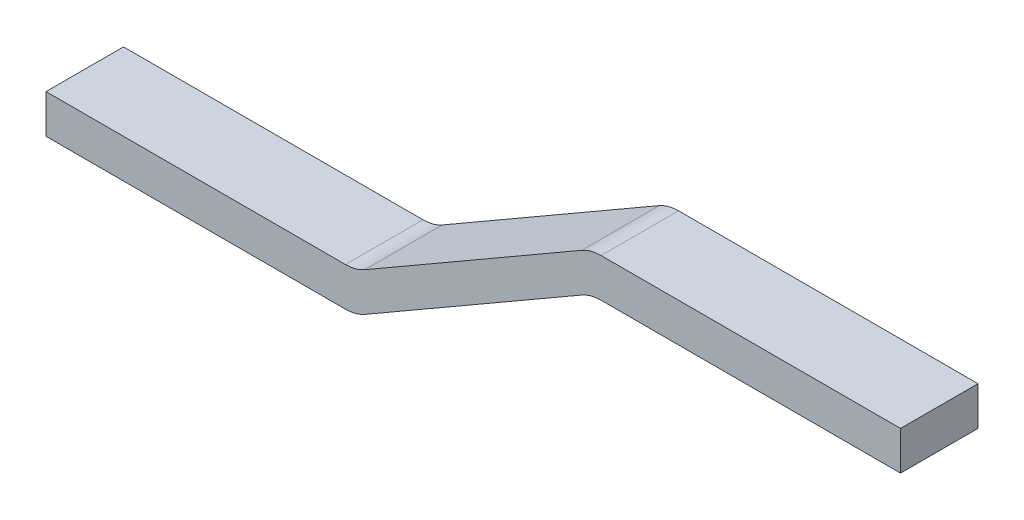
SolidWorks part; units mm, degrees
ref_plane "Plan de face" through (0, 0, 0) normal (0, 0, 1) x (1, 0, 0)
ref_plane "Plan de dessus" through (0, 0, 0) normal (0, 1, 0) x (1, 0, 0)
ref_plane "Plan de droite" through (0, 0, 0) normal (1, 0, 0) x (0, 0, -1)
sketch "Esquisse1" plane through (0, 0, 0) normal (0, 0, 1) x (1, 0, 0)
  line L0 (-20, 5) -> (20, 5)
  line L1 (20, 5) -> (50.3109, 22.5)
  line L2 (50.3109, 22.5) -> (90.3109, 22.5)
  line L3 (90.3109, 22.5) -> (90.3109, 17.5)
  line L4 (90.3109, 17.5) -> (50.3109, 17.5)
  line L5 (50.3109, 17.5) -> (20, 0)
  line L6 (20, 0) -> (-20, 0)
  line L7 (-20, 0) -> (-20, 5)
  point P10 (0, 0)
  dimension "D1" = 5
  dimension "D2" = 5
  dimension "D3" = 150
  dimension "D4" = 40
  dimension "D5" = 40
  dimension "D6" = 35
extrude "Boss.-Extru.1" add sketch "Esquisse1" along normal blind 10 contours L7 L0 L1 L2 L3 L4 L5 L6
fillet "Congé1" radius 5 4 edges at (50.3109, 17.5, 5) (50.3109, 22.5, 5) (20, 0, 5) (20, 5, 5)
